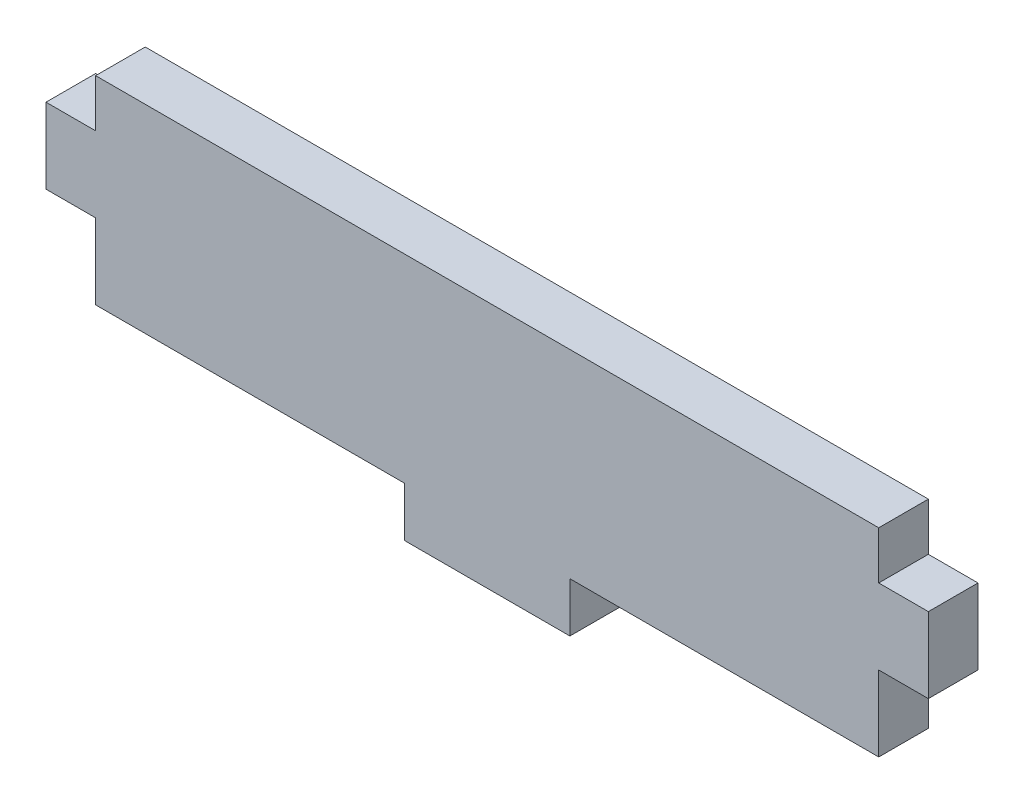
SolidWorks part; units mm, degrees
ref_plane "Front Plane" through (0, 0, 0) normal (0, 0, 1) x (1, 0, 0)
ref_plane "Top Plane" through (0, 0, 0) normal (0, 1, 0) x (1, 0, 0)
ref_plane "Right Plane" through (0, 0, 0) normal (1, 0, 0) x (0, 0, -1)
sketch "Sketch1" plane through (0, 0, 0) normal (0, 0, 1) x (1, 0, 0)
  line L0 (80, 45) -> (80, 0) construction
  line L1 (0, 0) -> (160, 0)
  line L2 (0, 0) -> (0, 45)
  line L3 (0, 45) -> (160, 45)
  line L4 (160, 0) -> (160, 45)
  line L5 (65, 4.5) -> (80, 4.5) construction
  line L6 (0, 9) -> (160, 9)
  line L7 (0, 9) -> (0, 0)
  line L8 (0, 0) -> (160, 0)
  line L9 (160, 9) -> (160, 0)
  line L10 (80, 4.5) -> (95, 4.5) construction
  line L11 (65, 9) -> (95, 9)
  line L12 (65, 9) -> (65, 0)
  line L13 (65, 0) -> (95, 0)
  line L14 (95, 9) -> (95, 0)
  line L15 (151, 36.3333) -> (151, 22.6667)
  line L16 (0, 36.3333) -> (9, 36.3333)
  line L17 (0, 36.3333) -> (0, 22.6667)
  line L18 (0, 22.6667) -> (9, 22.6667)
  line L19 (9, 36.3333) -> (9, 22.6667)
  line L20 (160, 22.6667) -> (151, 22.6667)
  line L21 (160, 36.3333) -> (160, 22.6667)
  line L22 (160, 36.3333) -> (151, 36.3333)
  line L23 (9, 45) -> (9, 9)
  line L24 (151, 9) -> (151, 45)
  dimension "D1" = 160
  dimension "45" = 45
  dimension "D3" = 9
  dimension "D4" = 30
  dimension "D5" = 9
  dimension "D6" = 13.6667
  dimension "D7" = 22.6667
extrude "Boss-Extrude1" add sketch "Sketch1" along normal blind 9 contours L6 L24 L15 L3 L23 L19 | L19 L16 L2 L18 | L14 L6 L12 L8 | L4 L22 L15 L20
equation "\"D6@Sketch1\"=41/3"
equation "\"D7@Sketch1\"=41/3+9"
equation "\"D1@Sketch1\"=160"
